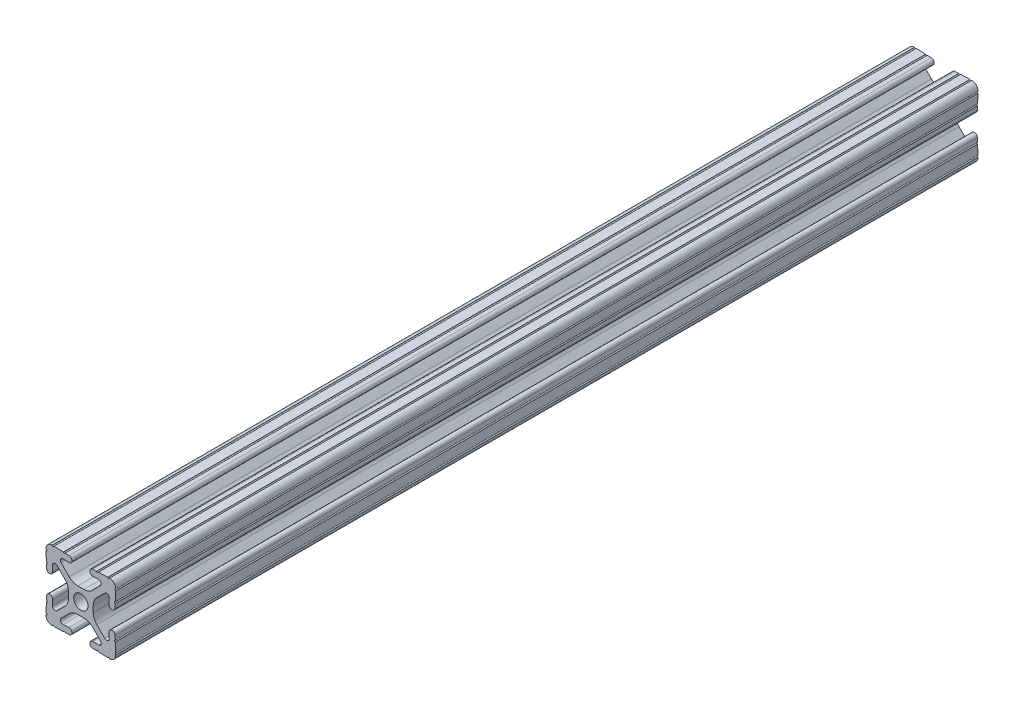
SolidWorks part; units mm, degrees
ref_plane "Front Plane" through (0, 0, 0) normal (0, 0, 1) x (1, 0, 0)
ref_plane "Top Plane" through (0, 0, 0) normal (0, 1, 0) x (1, 0, 0)
ref_plane "Right Plane" through (0, 0, 0) normal (1, 0, 0) x (0, 0, -1)
sketch "Sketch1" plane through (0, 0, 0) normal (0, 0, 1) x (1, 0, 0)
  line L0 (0, 12.7) -> (-12.7814, 12.7) construction
  line L1 (-4.5085, 0) -> (-4.5085, 2.9459)
  line L2 (-6.0437, 12.5461) -> (-10.0976, 12.6876) construction
  line L3 (-11.5616, 12.4229) -> (-4.3159, 12.1699) construction
  line L4 (-6.4364, 10.3486) -> (-6.3592, 12.5571) construction
  line L6 (-2.9459, 4.5085) -> (0, 4.5085)
  line L7 (0, 0) -> (0, 12.7) construction
  line L8 (0, 0) -> (-12.7814, 0) construction
  line L9 (0.7813, 0.7813) -> (-0.7813, -0.7813) construction
  line L10 (-2.9459, 4.5085) -> (-7.1484, 8.711)
  line L11 (-4.5085, 2.9459) -> (-8.711, 7.1484)
  line L13 (0, 0) -> (-12.7814, 12.7814) construction
  line L14 (-10.4131, 12.6987) -> (-4.3048, 12.4853)
  line L15 (-4.3048, 12.4853) -> (-4.382, 10.2769) construction
  line L16 (-4.382, 10.2769) -> (-6.4364, 10.3486)
  line L17 (-12.6987, 10.4131) -> (-12.4853, 4.3048)
  line L18 (-10.2769, 4.382) -> (-10.3486, 6.4364)
  circle A0 centre (0, 0) radius 2.6035
  arc A1 (-4.382, 10.2769) -> (-4.3048, 12.4853) centre (-4.3434, 11.3811) ccw
  arc A2 (-7.1484, 8.711) -> (-6.4364, 10.3486) centre (-6.4698, 9.3896) cw
  arc A3 (-8.711, 7.1484) -> (-10.3486, 6.4364) centre (-9.3896, 6.4698) ccw
  arc A4 (-10.2769, 4.382) -> (-12.4853, 4.3048) centre (-11.3811, 4.3434) cw
  arc A5 (-10.4131, 12.6987) -> (-12.6987, 10.4131) centre (-10.4902, 10.4902) ccw
  arc A6 (-10.4131, 12.6987) -> (-9.7821, 12.6766) centre (-10.0976, 12.6876) ccw
  arc A7 (-6.3592, 12.5571) -> (-5.7282, 12.5351) centre (-6.0437, 12.5461) ccw
  arc A8 (-12.5571, 6.3592) -> (-12.5351, 5.7282) centre (-12.5461, 6.0437) cw
  arc A9 (-12.6987, 10.4131) -> (-12.6766, 9.7821) centre (-12.6876, 10.0976) cw
  dimension "D1" = 5.207
  dimension "D5" = 14.859
  dimension "D9" = 2
  dimension "D2" = 25.4
  dimension "D12" = 0.6314
  dimension "D10" = 2.2098
  dimension "D3" = 9.017
  dimension "D4" = 9.017
  dimension "D6" = 25.4
  dimension "D7" = 6.477
  dimension "D8" = 2.2098
  dimension "D11" = 12.7
sketch "Sketch3" plane through (0, 0, 0) normal (0, 0, 1) x (1, 0, 0)
  line L0 (-2.9459, 4.5085) -> (0, 4.5085) construction
  line L1 (-2.9459, 4.5085) -> (-7.1484, 8.711) construction
  line L2 (-4.382, 10.2769) -> (-6.4364, 10.3486) construction
  line L3 (-10.4131, 12.6987) -> (-4.3048, 12.4853) construction
  line L4 (-4.5085, 0) -> (-4.5085, 2.9459) construction
  line L5 (-4.5085, 2.9459) -> (-8.711, 7.1484) construction
  line L6 (-10.2769, 4.382) -> (-10.3486, 6.4364) construction
  line L7 (-12.6987, 10.4131) -> (-12.4853, 4.3048) construction
  line L8 (-1.1153, 4.5085) -> (1.1153, 4.5085)
  line L9 (-4.2404, 5.803) -> (-7.1484, 8.711)
  line L10 (-4.382, 10.2769) -> (-6.4364, 10.3486)
  line L11 (-9.7821, 12.6766) -> (-6.3592, 12.5571)
  line L12 (-4.5085, -1.1153) -> (-4.5085, 1.1153)
  line L13 (-5.803, 4.2404) -> (-8.711, 7.1484)
  line L14 (-10.2769, 4.382) -> (-10.3486, 6.4364)
  line L15 (-12.6766, 9.7821) -> (-12.5571, 6.3592)
  line L16 (-5.7282, 12.5351) -> (-4.3048, 12.4853)
  line L17 (-12.5351, 5.7282) -> (-12.4853, 4.3048)
  line L18 (0, 0) -> (0, 12.7) construction
  line L19 (0, 0) -> (-12.7814, 0) construction
  line L20 (12.5351, 5.7282) -> (12.4853, 4.3048)
  line L21 (5.7282, 12.5351) -> (4.3048, 12.4853)
  line L22 (12.6766, 9.7821) -> (12.5571, 6.3592)
  line L23 (10.2769, 4.382) -> (10.3486, 6.4364)
  line L24 (5.803, 4.2404) -> (8.711, 7.1484)
  line L25 (4.5085, -1.1153) -> (4.5085, 1.1153)
  line L26 (9.7821, 12.6766) -> (6.3592, 12.5571)
  line L27 (4.382, 10.2769) -> (6.4364, 10.3486)
  line L28 (4.2404, 5.803) -> (7.1484, 8.711)
  line L29 (4.2404, -5.803) -> (7.1484, -8.711)
  line L30 (4.382, -10.2769) -> (6.4364, -10.3486)
  line L31 (9.7821, -12.6766) -> (6.3592, -12.5571)
  line L32 (5.803, -4.2404) -> (8.711, -7.1484)
  line L33 (10.2769, -4.382) -> (10.3486, -6.4364)
  line L34 (12.6766, -9.7821) -> (12.5571, -6.3592)
  line L35 (5.7282, -12.5351) -> (4.3048, -12.4853)
  line L36 (12.5351, -5.7282) -> (12.4853, -4.3048)
  line L37 (-12.5351, -5.7282) -> (-12.4853, -4.3048)
  line L38 (-5.7282, -12.5351) -> (-4.3048, -12.4853)
  line L39 (-12.6766, -9.7821) -> (-12.5571, -6.3592)
  line L40 (-10.2769, -4.382) -> (-10.3486, -6.4364)
  line L41 (-5.803, -4.2404) -> (-8.711, -7.1484)
  line L42 (-9.7821, -12.6766) -> (-6.3592, -12.5571)
  line L43 (-4.382, -10.2769) -> (-6.4364, -10.3486)
  line L44 (-4.2404, -5.803) -> (-7.1484, -8.711)
  line L45 (-1.1153, -4.5085) -> (1.1153, -4.5085)
  arc A0 (-10.4131, 12.6987) -> (-9.7821, 12.6766) centre (-10.0976, 12.6876) ccw construction
  arc A1 (-6.4364, 10.3486) -> (-7.1484, 8.711) centre (-6.4698, 9.3896) ccw construction
  arc A2 (-4.382, 10.2769) -> (-4.3048, 12.4853) centre (-4.3434, 11.3811) ccw construction
  arc A3 (-8.711, 7.1484) -> (-10.3486, 6.4364) centre (-9.3896, 6.4698) ccw construction
  arc A4 (-12.4853, 4.3048) -> (-10.2769, 4.382) centre (-11.3811, 4.3434) ccw construction
  arc A5 (-6.3592, 12.5571) -> (-5.7282, 12.5351) centre (-6.0437, 12.5461) ccw construction
  arc A6 (-10.4131, 12.6987) -> (-12.6987, 10.4131) centre (-10.4902, 10.4902) ccw construction
  arc A7 (-12.6766, 9.7821) -> (-12.6987, 10.4131) centre (-12.6876, 10.0976) ccw construction
  arc A8 (-12.5351, 5.7282) -> (-12.5571, 6.3592) centre (-12.5461, 6.0437) ccw construction
  arc A9 (-10.4131, 12.6987) -> (-9.7821, 12.6766) centre (-10.0976, 12.6876) ccw
  arc A10 (-6.4364, 10.3486) -> (-7.1484, 8.711) centre (-6.4698, 9.3896) ccw
  arc A11 (-4.382, 10.2769) -> (-4.3048, 12.4853) centre (-4.3434, 11.3811) ccw
  arc A12 (-8.711, 7.1484) -> (-10.3486, 6.4364) centre (-9.3896, 6.4698) ccw
  arc A13 (-12.4853, 4.3048) -> (-10.2769, 4.382) centre (-11.3811, 4.3434) ccw
  arc A14 (-6.3592, 12.5571) -> (-5.7282, 12.5351) centre (-6.0437, 12.5461) ccw
  arc A15 (-10.4131, 12.6987) -> (-12.6987, 10.4131) centre (-10.4902, 10.4902) ccw
  arc A16 (-12.6766, 9.7821) -> (-12.6987, 10.4131) centre (-12.6876, 10.0976) ccw
  arc A17 (-12.5351, 5.7282) -> (-12.5571, 6.3592) centre (-12.5461, 6.0437) ccw
  arc A18 (-1.1153, 4.5085) -> (-4.2404, 5.803) centre (-1.1153, 8.9281) cw
  arc A19 (4.5085, 1.1153) -> (5.803, 4.2404) centre (8.9281, 1.1153) cw
  arc A20 (1.1153, 4.5085) -> (4.2404, 5.803) centre (1.1153, 8.9281) ccw
  arc A21 (-4.5085, 1.1153) -> (-5.803, 4.2404) centre (-8.9281, 1.1153) ccw
  arc A22 (12.5351, 5.7282) -> (12.5571, 6.3592) centre (12.5461, 6.0437) cw
  arc A23 (12.6766, 9.7821) -> (12.6987, 10.4131) centre (12.6876, 10.0976) cw
  arc A24 (10.4131, 12.6987) -> (12.6987, 10.4131) centre (10.4902, 10.4902) cw
  arc A25 (6.3592, 12.5571) -> (5.7282, 12.5351) centre (6.0437, 12.5461) cw
  arc A26 (12.4853, 4.3048) -> (10.2769, 4.382) centre (11.3811, 4.3434) cw
  arc A27 (8.711, 7.1484) -> (10.3486, 6.4364) centre (9.3896, 6.4698) cw
  arc A28 (4.382, 10.2769) -> (4.3048, 12.4853) centre (4.3434, 11.3811) cw
  arc A29 (6.4364, 10.3486) -> (7.1484, 8.711) centre (6.4698, 9.3896) cw
  arc A30 (10.4131, 12.6987) -> (9.7821, 12.6766) centre (10.0976, 12.6876) cw
  arc A31 (10.4131, -12.6987) -> (9.7821, -12.6766) centre (10.0976, -12.6876) ccw
  arc A32 (6.4364, -10.3486) -> (7.1484, -8.711) centre (6.4698, -9.3896) ccw
  arc A33 (4.382, -10.2769) -> (4.3048, -12.4853) centre (4.3434, -11.3811) ccw
  arc A34 (8.711, -7.1484) -> (10.3486, -6.4364) centre (9.3896, -6.4698) ccw
  arc A35 (12.4853, -4.3048) -> (10.2769, -4.382) centre (11.3811, -4.3434) ccw
  arc A36 (6.3592, -12.5571) -> (5.7282, -12.5351) centre (6.0437, -12.5461) ccw
  arc A37 (10.4131, -12.6987) -> (12.6987, -10.4131) centre (10.4902, -10.4902) ccw
  arc A38 (12.6766, -9.7821) -> (12.6987, -10.4131) centre (12.6876, -10.0976) ccw
  arc A39 (12.5351, -5.7282) -> (12.5571, -6.3592) centre (12.5461, -6.0437) ccw
  arc A40 (-4.5085, -1.1153) -> (-5.803, -4.2404) centre (-8.9281, -1.1153) cw
  arc A41 (1.1153, -4.5085) -> (4.2404, -5.803) centre (1.1153, -8.9281) cw
  arc A42 (4.5085, -1.1153) -> (5.803, -4.2404) centre (8.9281, -1.1153) ccw
  arc A43 (-1.1153, -4.5085) -> (-4.2404, -5.803) centre (-1.1153, -8.9281) ccw
  arc A44 (-12.5351, -5.7282) -> (-12.5571, -6.3592) centre (-12.5461, -6.0437) cw
  arc A45 (-12.6766, -9.7821) -> (-12.6987, -10.4131) centre (-12.6876, -10.0976) cw
  arc A46 (-10.4131, -12.6987) -> (-12.6987, -10.4131) centre (-10.4902, -10.4902) cw
  arc A47 (-6.3592, -12.5571) -> (-5.7282, -12.5351) centre (-6.0437, -12.5461) cw
  arc A48 (-12.4853, -4.3048) -> (-10.2769, -4.382) centre (-11.3811, -4.3434) cw
  arc A49 (-8.711, -7.1484) -> (-10.3486, -6.4364) centre (-9.3896, -6.4698) cw
  arc A50 (-4.382, -10.2769) -> (-4.3048, -12.4853) centre (-4.3434, -11.3811) cw
  arc A51 (-6.4364, -10.3486) -> (-7.1484, -8.711) centre (-6.4698, -9.3896) cw
  arc A52 (-10.4131, -12.6987) -> (-9.7821, -12.6766) centre (-10.0976, -12.6876) cw
  circle A53 centre (0, 0) radius 2.6035 construction
  circle A54 centre (0, 0) radius 2.6035
  point P135 (4.5085, 0)
  dimension "D2" = 4.4196
extrude "Extrude1" add sketch "Sketch3" along normal mid plane 314.1
equation "\"D10@Sketch1\" = \"D8@Sketch1\""
equation "\"D11@Sketch1\" = \"D6@Sketch1\"/2"
equation "\"D12@Sketch1\" = \"D8@Sketch1\"/3.5"
equation "\"D2@Sketch3\" = \"D8@Sketch1\"*2"
